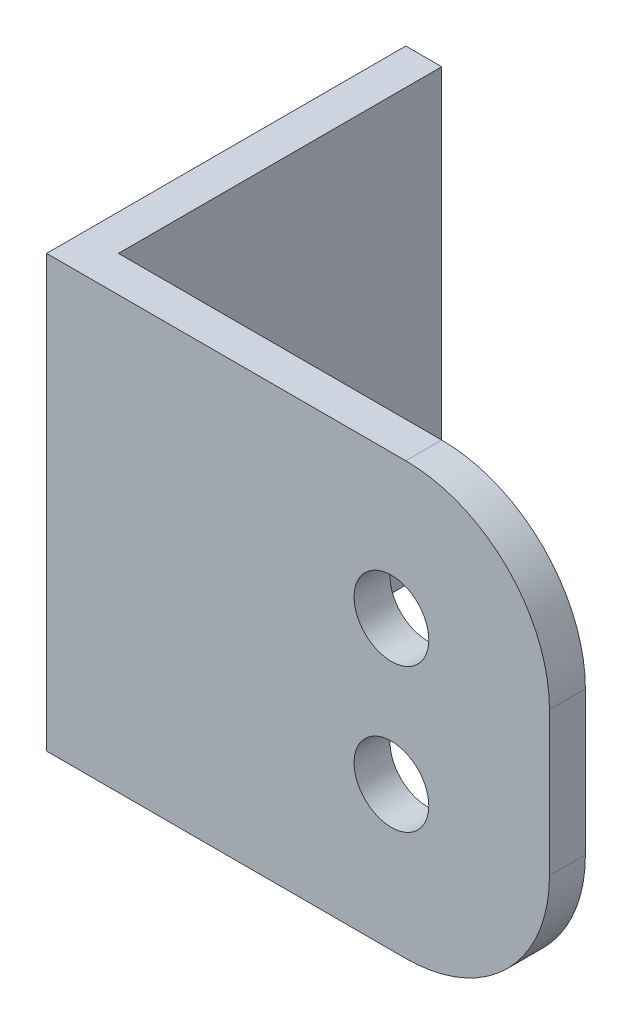
SolidWorks part; units mm, degrees
material "AISI 4130 Steel, annealed at 865C"
ref_plane "Front Plane" through (0, 0, 0) normal (0, 0, 1) x (1, 0, 0)
ref_plane "Top Plane" through (0, 0, 0) normal (0, 1, 0) x (1, 0, 0)
ref_plane "Right Plane" through (0, 0, 0) normal (1, 0, 0) x (0, 0, -1)
sketch "Sketch1" plane through (0, 0, 0) normal (0, 0, 1) x (1, 0, 0)
  line L0 (0, -374.8954) -> (0, 18369.8741) construction
  line L6 (0, 19.05) -> (44.45, 19.05)
  line L7 (0, 19.05) -> (0, -19.05)
  line L8 (0, -19.05) -> (44.45, -19.05)
  line L9 (44.45, 19.05) -> (44.45, -19.05)
  line L10 (22.225, -19.05) -> (22.225, 19.05) construction
  line L11 (0, 0) -> (44.45, 0) construction
  point P291 (22.225, 0)
  dimension "D1" = 44.45
  dimension "D2" = 38.1
extrude "Boss-Extrude1" add sketch "Sketch1" along normal blind 3.175
sketch "Sketch2" plane through (0, 0, 3.175) normal (0, 0, 1) x (1, 0, 0)
  line L0 (30.48, 6.35) -> (30.48, -6.35) construction
  line L1 (0, 0) -> (44.45, 0) construction
  line L2 (0, 19.05) -> (0, -19.05) construction
  line L3 (44.45, -19.05) -> (44.45, 19.05) construction
  circle A0 centre (30.48, 6.35) radius 3.302
  circle A1 centre (30.48, -6.35) radius 3.302
  point P4 (30.48, 0)
  dimension "D1" = 6.604
  dimension "D2" = 30.48
  dimension "D3" = 12.7
extrude "Cut-Extrude1" cut sketch "Sketch2" against normal through all both and the other way through all
sketch "Sketch3" plane through (0, 0, 0) normal (0, 0, -1) x (-1, 0, 0)
  line L0 (0, -19.05) -> (-44.45, -19.05) construction
  line L1 (0, 19.05) -> (-3.175, 19.05)
  line L2 (0, 19.05) -> (0, -19.05)
  line L3 (0, -19.05) -> (-3.175, -19.05)
  line L4 (-3.175, 19.05) -> (-3.175, -19.05)
  line L5 (-1.5875, -19.05) -> (-1.5875, 19.05) construction
  line L6 (0, 0) -> (-3.175, 0) construction
  point P148 (-1.5875, 0)
  dimension "D1" = 3.175
extrude "Boss-Extrude2" add sketch "Sketch3" along normal blind 28.575
fillet "Fillet1" radius 12.7 2 edges at (44.45, -19.05, 1.5875) (44.45, 19.05, 1.5875)
